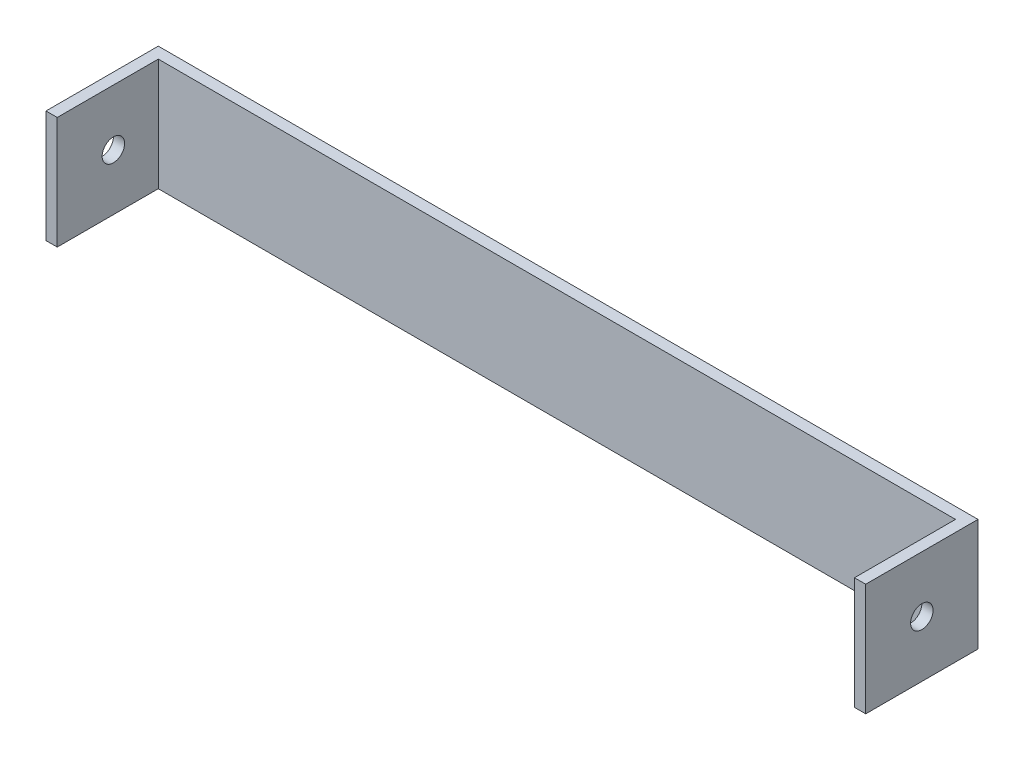
SolidWorks part; units mm, degrees
ref_plane "Front Plane" through (0, 0, 0) normal (0, 0, 1) x (1, 0, 0)
ref_plane "Top Plane" through (0, 0, 0) normal (0, 1, 0) x (1, 0, 0)
ref_plane "Right Plane" through (0, 0, 0) normal (1, 0, 0) x (0, 0, -1)
sketch "Sketch1" plane through (0, 0, 0) normal (0, 0, 1) x (1, 0, 0)
  line L1 (-73, 10) -> (73, 10)
  line L2 (-73, 10) -> (-73, -10)
  line L3 (-73, -10) -> (73, -10)
  line L4 (73, 10) -> (73, -10)
  line L5 (-73, 10) -> (73, -10) construction
  line L6 (-73, -10) -> (73, 10) construction
  point P0 (0, 0)
  dimension "D1" = 20
  dimension "D2" = 146
extrude "Boss-Extrude1" add sketch "Sketch1" along normal blind 2
sketch "Sketch2" plane through (0, 0, 2) normal (0, 0, 1) x (1, 0, 0)
  line L0 (-73, -10) -> (73, -10) construction
  line L1 (73, 10) -> (71, 10)
  line L2 (73, 10) -> (73, -10)
  line L3 (73, -10) -> (71, -10)
  line L4 (71, 10) -> (71, -10)
  line L6 (-73, 10) -> (-71, 10)
  line L7 (-73, 10) -> (-73, -10)
  line L8 (-73, -10) -> (-71, -10)
  line L9 (-71, 10) -> (-71, -10)
  dimension "D1" = 2
  dimension "D2" = 2
extrude "Boss-Extrude2" add sketch "Sketch2" along normal blind 18
sketch "Sketch3" plane through (-73, 0, 0) normal (-1, 0, 0) x (0, 0, 1)
  line L0 (0, 10) -> (0, -10) construction
  circle A0 centre (10, 0) radius 2
  dimension "D1" = 4
  dimension "D2" = 10
extrude "Cut-Extrude1" cut sketch "Sketch3" against normal through all and the other way through all
